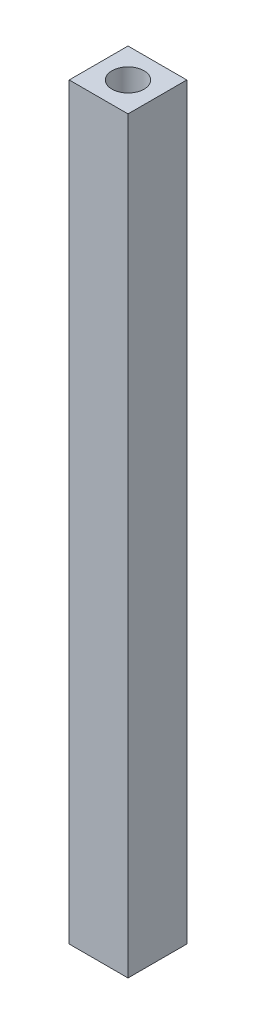
SolidWorks part; units mm, degrees
ref_plane "Front Plane" through (0, 0, 0) normal (0, 0, 1) x (1, 0, 0)
ref_plane "Top Plane" through (0, 0, 0) normal (0, 1, 0) x (1, 0, 0)
ref_plane "Right Plane" through (0, 0, 0) normal (1, 0, 0) x (0, 0, -1)
sketch "Sketch1" plane through (0, 0, 0) normal (0, 1, 0) x (1, 0, 0)
  line L1 (-2.75, 2.75) -> (2.75, 2.75)
  line L2 (-2.75, 2.75) -> (-2.75, -2.75)
  line L3 (-2.75, -2.75) -> (2.75, -2.75)
  line L4 (2.75, 2.75) -> (2.75, -2.75)
  line L5 (-2.75, 2.75) -> (2.75, -2.75) construction
  line L6 (-2.75, -2.75) -> (2.75, 2.75) construction
  point P0 (0, 0)
  dimension "D1" = 5.5
extrude "Boss-Extrude1" add sketch "Sketch1" along normal mid plane 70
sketch "Sketch3" plane through (0, 35, 0) normal (0, 1, 0) x (1, 0, 0)
  circle A0 centre (0, 0) radius 1.5
  dimension "D1" = 3
extrude "Cut-Extrude1" cut sketch "Sketch3" against normal blind 10
mirror "Mirror1" about plane through (0, 0, 0) normal (0, 1, 0) of "Cut-Extrude1"
